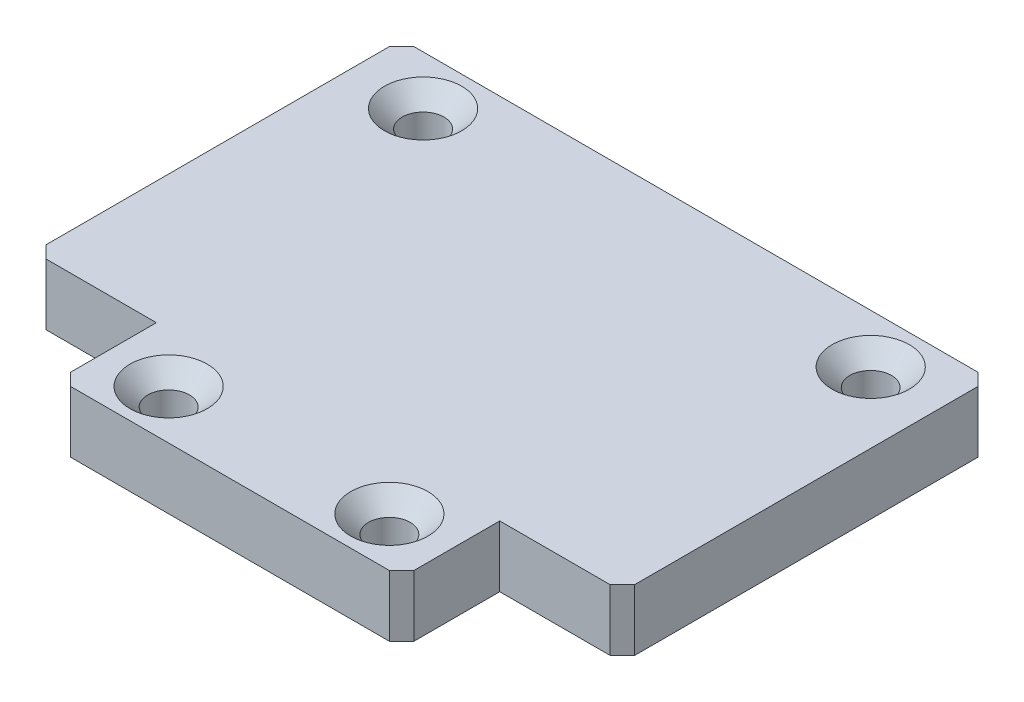
SolidWorks part; units mm, degrees
material "PE High Density"
ref_plane "Front Plane" through (0, 0, 0) normal (0, 0, 1) x (1, 0, 0)
ref_plane "Top Plane" through (0, 0, 0) normal (0, 1, 0) x (1, 0, 0)
ref_plane "Right Plane" through (0, 0, 0) normal (1, 0, 0) x (0, 0, -1)
sketch "Sketch1" plane through (0, 0, 0) normal (0, 1, 0) x (1, 0, 0)
  line L0 (0, 0) -> (0, 30)
  line L1 (0, 30) -> (48, 30)
  line L2 (48, 30) -> (48, 0)
  line L3 (48, 0) -> (38, 0)
  line L4 (38, 0) -> (38, -8)
  line L5 (38, -8) -> (10, -8)
  line L6 (10, -8) -> (10, 0)
  line L7 (10, 0) -> (0, 0)
  line L8 (24, 30) -> (24, -8) construction
  dimension "D1" = 48
  dimension "D2" = 30
  dimension "D3" = 8
  dimension "D4" = 28
extrude "Boss-Extrude1" add sketch "Sketch1" along normal blind 5
hole_wizard "CSK for M3 Flat Countersunk Head Screw1" positions "Sketch2" profile "Sketch3" countersink size "M3" standard "JIS" end condition through all
sketch "Sketch2" plane through (0, 5, 0) normal (0, 1, 0) x (1, 0, 0)
  line L0 (24, 30) -> (24, -8) construction
  line L1 (48, 30) -> (0, 30) construction
  line L2 (10, -8) -> (38, -8) construction
  point P0 (5.75, 26)
  point P2 (42.25, 26)
  point P4 (15, -4)
  point P6 (33, -4)
  dimension "D1" = 36.5
  dimension "D2" = 18
  dimension "D3" = 4
  dimension "D4" = 34
sketch "Sketch3" plane through (5.75, 5, -26) normal (1, 0, 0) x (0, 0, 1)
  line L0 (0, 0) -> (0, 5)
  line L1 (0, 5) -> (1.7, 5)
  line L2 (1.7, 5) -> (1.7, 1.45)
  line L3 (1.7, 1.45) -> (3.15, 0)
  line L5 (3.15, 0) -> (0, 0)
  line L6 (-1.7, 1.45) -> (-3.15, 0) construction
  line L11 (0, -6.35) -> (0, 107.95) construction
  dimension "Thru Hole Dia." = 3.4
  dimension "Thru Hole Depth" = 5
  dimension "Near C'Sink Dia." = 6.3
  dimension "Near C'Sink Angle" = 90
chamfer "Chamfer1" distance 1 angle 45 6 edges at (0, 2.5, -30) (48, 2.5, -30) (48, 2.5, 0) (38, 2.5, 8) (10, 2.5, 8) (0, 2.5, 0)
